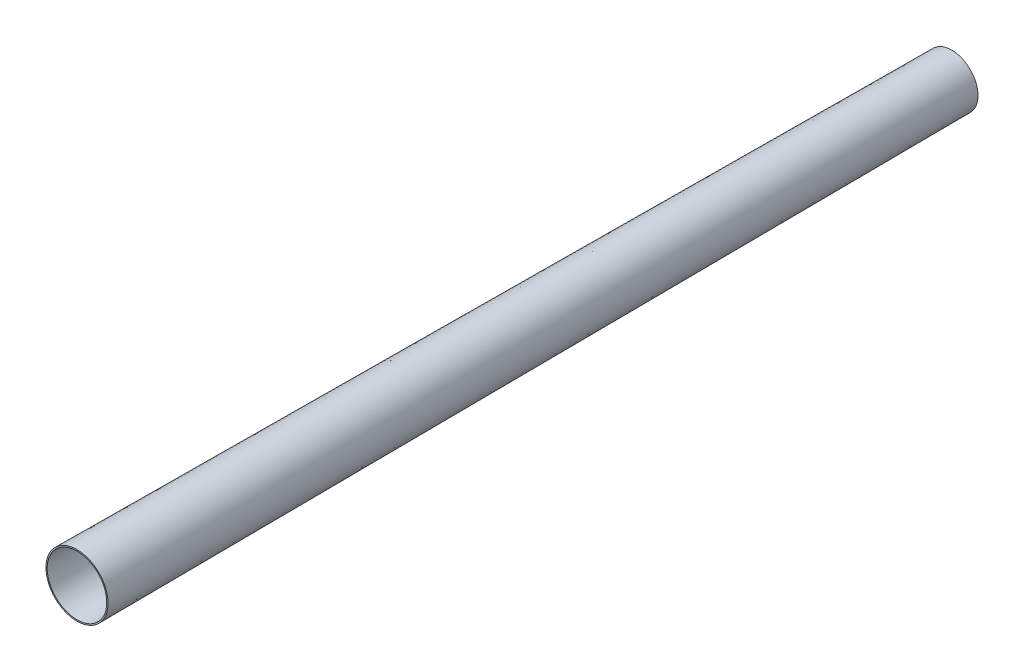
SolidWorks part; units mm, degrees
ref_plane "Front Plane" through (0, 0, 0) normal (0, 0, 1) x (1, 0, 0)
ref_plane "Top Plane" through (0, 0, 0) normal (0, 1, 0) x (1, 0, 0)
ref_plane "Right Plane" through (0, 0, 0) normal (1, 0, 0) x (0, 0, -1)
sketch "Sketch1" plane through (0, 0, 0) normal (0, 0, 1) x (1, 0, 0)
  circle A0 centre (0, 0) radius 9.992
  circle A1 centre (0, 0) radius 10.492
  dimension "D2" = 20.9841
  dimension "D1" = 0.5
ref_plane "Plane1" through (0, 0, 349.7002) normal (0, 0, 1) x (1, 0, 0)
sketch "Sketch2" plane through (0, 0, 349.7002) normal (0, 0, 1) x (1, 0, 0)
  circle A0 centre (0, 0) radius 12.4044
  circle A1 centre (0, 0) radius 11.9044
  dimension "D2" = 24.8088
  dimension "D1" = 0.5
loft "Loft1" add section "Sketch1" section "Sketch2"
shell "Shell1" thickness 0.5
